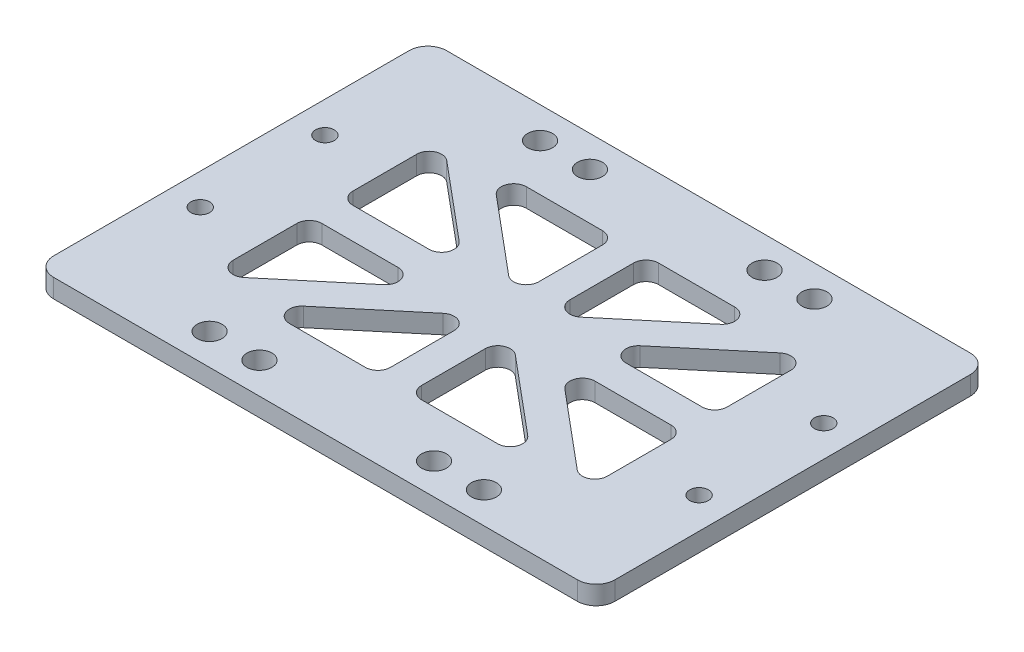
SolidWorks part; units mm, degrees
ref_plane "前视基准面" through (0, 0, 0) normal (0, 0, 1) x (1, 0, 0)
ref_plane "上视基准面" through (0, 0, 0) normal (0, 1, 0) x (1, 0, 0)
ref_plane "右视基准面" through (0, 0, 0) normal (1, 0, 0) x (0, 0, -1)
other "Configuration Table"
sketch "草图1" plane through (0, 0, 0) normal (0, 1, 0) x (1, 0, 0)
  line L1 (-45, 31.5) -> (45, 31.5)
  line L2 (-45, 31.5) -> (-45, -31.5)
  line L3 (-45, -31.5) -> (45, -31.5)
  line L4 (45, 31.5) -> (45, -31.5)
  line L5 (-45, 31.5) -> (45, -31.5) construction
  line L6 (-45, -31.5) -> (45, 31.5) construction
  point P0 (0, 0)
  dimension "D1" = 90
  dimension "D2" = 63
extrude "凸台-拉伸1" add sketch "草图1" along normal blind 3
fillet "圆角1" radius 3 4 edges at (-45, 1.5, 31.5) (-45, 1.5, -31.5) (45, 1.5, -31.5) (45, 1.5, 31.5)
sketch "草图2" plane through (0, 3, 0) normal (0, 1, 0) x (1, 0, 0)
  line L0 (0, 0) -> (0, 31.5) construction
  line L1 (42, 31.5) -> (-42, 31.5) construction
  line L2 (0, 0) -> (-45, 0) construction
  line L3 (-45, 28.5) -> (-45, -28.5) construction
  line L4 (-42, -31.5) -> (42, -31.5) construction
  line L5 (22, -26.5) -> (14, -26.5) construction
  line L6 (-35, -31.5) -> (-1, -31.5) construction
  line L7 (-35, -31.5) -> (-35, -21.5) construction
  line L8 (-35, -21.5) -> (-1, -21.5) construction
  line L9 (-1, -31.5) -> (-1, -21.5) construction
  line L10 (-22, -26.5) -> (-14, -26.5) construction
  line L11 (1, -31.5) -> (1, -21.5) construction
  line L12 (35, -21.5) -> (1, -21.5) construction
  line L13 (35, -31.5) -> (35, -21.5) construction
  line L14 (35, -31.5) -> (1, -31.5) construction
  line L15 (35, 31.5) -> (1, 31.5) construction
  line L16 (35, 31.5) -> (35, 21.5) construction
  line L17 (35, 21.5) -> (1, 21.5) construction
  line L18 (1, 31.5) -> (1, 21.5) construction
  line L19 (-22, 26.5) -> (-14, 26.5) construction
  line L20 (-1, 31.5) -> (-1, 21.5) construction
  line L21 (-35, 21.5) -> (-1, 21.5) construction
  line L22 (-35, 31.5) -> (-35, 21.5) construction
  line L23 (-35, 31.5) -> (-1, 31.5) construction
  line L24 (22, 26.5) -> (14, 26.5) construction
  circle A0 centre (-40, 10) radius 1.5
  circle A1 centre (-40, -10) radius 1.5
  circle A3 centre (40, -10) radius 1.5
  circle A4 centre (40, 10) radius 1.5
  circle A5 centre (-22, -26.5) radius 2
  circle A6 centre (-14, -26.5) radius 2
  circle A9 centre (14, -26.5) radius 2
  circle A10 centre (22, -26.5) radius 2
  circle A11 centre (22, 26.5) radius 2
  circle A12 centre (14, 26.5) radius 2
  circle A13 centre (-14, 26.5) radius 2
  circle A14 centre (-22, 26.5) radius 2
  dimension "D1" = 3
  dimension "D9" = 4
  dimension "D2" = 5
  dimension "D3" = 20
  dimension "D4" = 10
  dimension "D5" = 10
  dimension "D6" = 34
  dimension "D7" = 13
  dimension "D8" = 8
  dimension "D10" = 5
extrude "切除-拉伸1" cut sketch "草图2" against normal blind 10
sketch "草图4" plane through (0, 3, 0) normal (0, 1, 0) x (1, 0, 0)
  line L0 (16.7056, -19) -> (4.5, -19)
  line L1 (2.5, -17) -> (2.5, -6.7825)
  line L2 (5.7838, -5.2489) -> (17.9894, -15.4664)
  line L3 (0, 0) -> (0, 31.5) construction
  line L4 (42, 31.5) -> (-42, 31.5) construction
  line L5 (0, 0) -> (45, 0) construction
  line L6 (45, -28.5) -> (45, 28.5) construction
  line L7 (-42, -31.5) -> (42, -31.5) construction
  line L8 (14.5106, -6.0336) -> (26.7162, -16.2511)
  line L9 (30, -14.7175) -> (30, -4.5)
  line L10 (28, -2.5) -> (15.7944, -2.5)
  line L11 (28, 2.5) -> (15.7944, 2.5)
  line L12 (30, 14.7175) -> (30, 4.5)
  line L13 (14.5106, 6.0336) -> (26.7162, 16.2511)
  line L14 (5.7838, 5.2489) -> (17.9894, 15.4664)
  line L15 (2.5, 17) -> (2.5, 6.7825)
  line L16 (16.7056, 19) -> (4.5, 19)
  line L17 (-16.7056, 19) -> (-4.5, 19)
  line L18 (-2.5, 17) -> (-2.5, 6.7825)
  line L19 (-5.7838, 5.2489) -> (-17.9894, 15.4664)
  line L20 (-14.5106, 6.0336) -> (-26.7162, 16.2511)
  line L21 (-30, 14.7175) -> (-30, 4.5)
  line L22 (-28, 2.5) -> (-15.7944, 2.5)
  line L23 (-28, -2.5) -> (-15.7944, -2.5)
  line L24 (-30, -14.7175) -> (-30, -4.5)
  line L25 (-14.5106, -6.0336) -> (-26.7162, -16.2511)
  line L26 (-5.7838, -5.2489) -> (-17.9894, -15.4664)
  line L27 (-2.5, -17) -> (-2.5, -6.7825)
  line L28 (-16.7056, -19) -> (-4.5, -19)
  arc A0 (16.7056, -19) -> (17.9894, -15.4664) centre (16.7056, -17) ccw
  arc A1 (4.5, -19) -> (2.5, -17) centre (4.5, -17) cw
  arc A2 (2.5, -6.7825) -> (5.7838, -5.2489) centre (4.5, -6.7825) cw
  arc A3 (30, -4.5) -> (28, -2.5) centre (28, -4.5) ccw
  arc A4 (26.7162, -16.2511) -> (30, -14.7175) centre (28, -14.7175) ccw
  arc A5 (14.5106, -6.0336) -> (15.7944, -2.5) centre (15.7944, -4.5) cw
  arc A6 (14.5106, 6.0336) -> (15.7944, 2.5) centre (15.7944, 4.5) ccw
  arc A7 (26.7162, 16.2511) -> (30, 14.7175) centre (28, 14.7175) cw
  arc A8 (30, 4.5) -> (28, 2.5) centre (28, 4.5) cw
  arc A9 (2.5, 6.7825) -> (5.7838, 5.2489) centre (4.5, 6.7825) ccw
  arc A10 (4.5, 19) -> (2.5, 17) centre (4.5, 17) ccw
  arc A11 (16.7056, 19) -> (17.9894, 15.4664) centre (16.7056, 17) cw
  arc A12 (-16.7056, 19) -> (-17.9894, 15.4664) centre (-16.7056, 17) ccw
  arc A13 (-4.5, 19) -> (-2.5, 17) centre (-4.5, 17) cw
  arc A14 (-2.5, 6.7825) -> (-5.7838, 5.2489) centre (-4.5, 6.7825) cw
  arc A15 (-30, 4.5) -> (-28, 2.5) centre (-28, 4.5) ccw
  arc A16 (-26.7162, 16.2511) -> (-30, 14.7175) centre (-28, 14.7175) ccw
  arc A17 (-14.5106, 6.0336) -> (-15.7944, 2.5) centre (-15.7944, 4.5) cw
  arc A18 (-14.5106, -6.0336) -> (-15.7944, -2.5) centre (-15.7944, -4.5) ccw
  arc A19 (-26.7162, -16.2511) -> (-30, -14.7175) centre (-28, -14.7175) cw
  arc A20 (-30, -4.5) -> (-28, -2.5) centre (-28, -4.5) cw
  arc A21 (-2.5, -6.7825) -> (-5.7838, -5.2489) centre (-4.5, -6.7825) ccw
  arc A22 (-4.5, -19) -> (-2.5, -17) centre (-4.5, -17) ccw
  arc A23 (-16.7056, -19) -> (-17.9894, -15.4664) centre (-16.7056, -17) cw
  point P11 (30, -14.3828)
  point P17 (26.4314, -16.5)
  point P18 (0, 0)
  point P19 (0, 0)
  point P20 (10.5196, -5)
  point P21 (21.4146, -16.5)
  point P22 (3.2732, -16.5)
  point P29 (2.5, -2.5)
  point P34 (30, -19)
  point P55 (30, 19)
  point P56 (2.5, 2.5)
  point P93 (-2.5, 2.5)
  point P94 (-30, 19)
  point P95 (-30, -19)
  point P96 (-2.5, -2.5)
  dimension "D6" = 2
  dimension "D1" = 12.5
  dimension "D2" = 2.5
  dimension "D3" = 15
  dimension "D4" = 5
  dimension "D5" = 2.5
extrude "切除-拉伸2" cut sketch "草图4" against normal blind 10
